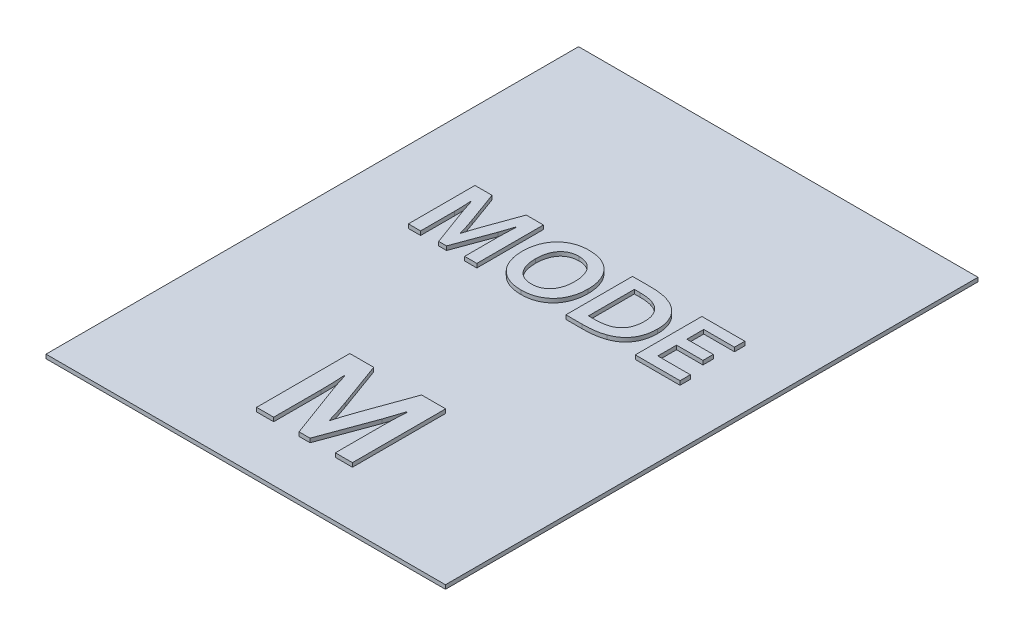
SolidWorks part; units mm, degrees
ref_plane "Front Plane" through (0, 0, 0) normal (0, 0, 1) x (1, 0, 0)
ref_plane "Top Plane" through (0, 0, 0) normal (0, 1, 0) x (1, 0, 0)
ref_plane "Right Plane" through (0, 0, 0) normal (1, 0, 0) x (0, 0, -1)
sketch "Sketch1" plane through (0, 0, 0) normal (0, 1, 0) x (1, 0, 0)
  line L1 (0, 0) -> (15, 0)
  line L2 (0, 0) -> (0, 20)
  line L3 (0, 20) -> (15, 20)
  line L4 (15, 0) -> (15, 20)
  dimension "D1" = 20
  dimension "D2" = 15
extrude "Boss-Extrude1" add sketch "Sketch1" along normal blind 0.15
sketch "Sketch2" plane through (0, 0.15, 0) normal (0, 1, 0) x (1, 0, 0)
  line L0 (2.4364, 10.891) -> (16.9687, 10.891) construction
  line L1 (0.9398, 2.0749) -> (14.3282, 2.0749) construction
  text T0 "<b>MODE</b>" font "Corbel" height 2.5
  text T1 "<b>M</b>" font "Corbel" height 3.5
  point P5 (2.0525, 2.1845)
  point P6 (0.9398, 2.1387)
  point P7 (14.3282, 2.0749)
extrude "Boss-Extrude2" add sketch "Sketch2" along normal blind 0.15
